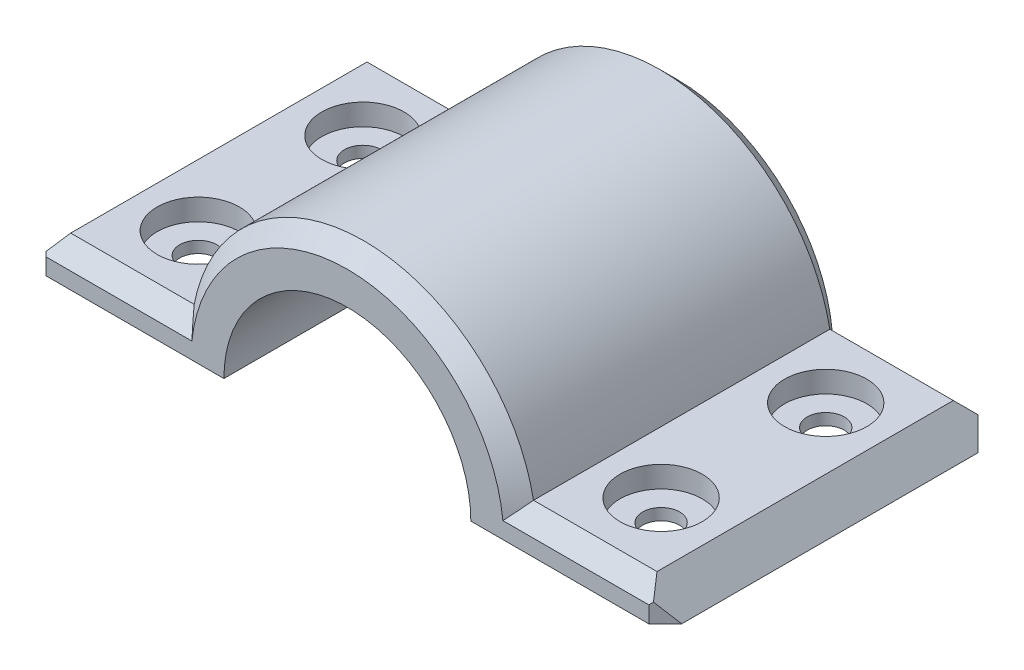
SolidWorks part; units mm, degrees
material "ABS"
ref_plane "Piano frontale" through (0, 0, 0) normal (0, 0, 1) x (1, 0, 0)
ref_plane "Piano superiore" through (0, 0, 0) normal (0, 1, 0) x (1, 0, 0)
ref_plane "Piano destro" through (0, 0, 0) normal (1, 0, 0) x (0, 0, -1)
sketch "Schizzo1" plane through (0, 0, 0) normal (0, 0, 1) x (1, 0, 0)
  line L0 (-14.6572, -3.1885) -> (-11, -20) construction
  line L1 (-11, -20) -> (11, -20) construction
  line L2 (11, -20) -> (14.6572, -3.1885) construction
  line L3 (-14.6572, -3.1885) -> (14.6572, -3.1885) construction
  line L4 (0, -20) -> (0, 0) construction
  line L5 (-15, 0) -> (15, 0) construction
  line L8 (-15, 0) -> (-38.6155, 0)
  line L9 (-38.6155, 0) -> (-35.6155, 4)
  line L10 (-35.6155, 4) -> (-20.6155, 4)
  line L11 (15, 0) -> (38.6155, 0)
  line L12 (38.6155, 0) -> (35.6155, 4)
  line L13 (35.6155, 4) -> (20.6155, 4)
  arc A0 (15, 0) -> (-15, 0) centre (0, 0) ccw construction
  arc A1 (20.6155, 4) -> (-20.6155, 4) centre (0, 0) ccw
  arc A2 (15, 0) -> (-15, 0) centre (0, 0) ccw
  arc A3 (-14.6572, -3.1885) -> (-15, 0) centre (0, 0) cw construction
  arc A4 (14.6572, -3.1885) -> (15, 0) centre (0, 0) ccw construction
  point P8 (0, -3.1885)
  dimension "D2" = 15
  dimension "D4" = 6
  dimension "D1" = 22
  dimension "D3" = 20
  dimension "D5" = 4
  dimension "D6" = 15
  dimension "D7" = 3
extrude "Estrusione-Estrusione1" add sketch "Schizzo1" along normal blind 40
sketch "Schizzo2" plane through (0, 4, 0) normal (0, 1, 0) x (1, 0, 0)
  line L0 (-28.1155, -30) -> (-28.1155, -10) construction
  line L1 (-28.1155, -10) -> (28.1155, -10) construction
  line L2 (28.1155, -10) -> (28.1155, -30) construction
  line L3 (28.1155, -30) -> (-28.1155, -30) construction
  line L5 (-28.1155, -30) -> (-28.1155, -40) construction
  line L6 (-20.6155, -40) -> (-35.6155, -40) construction
  line L8 (-35.6155, -20) -> (-28.1155, -20) construction
  line L9 (-35.6155, -40) -> (-35.6155, 0) construction
  line L11 (28.1155, -10) -> (28.1155, 0) construction
  line L12 (35.6155, 0) -> (20.6155, 0) construction
  line L14 (-20.6155, 0) -> (-35.6155, 0) construction
  point P0 (-28.1155, -10)
  point P2 (-28.1155, -30)
  point P4 (28.1155, -30)
  point P6 (28.1155, -10)
  dimension "D1" = 10
hole_wizard "Foro lamato per Vite M4 a testa cilindrica-1" positions "Schizzo2" profile "Schizzo3" counterbore size "M4" standard "DIN"
sketch "Schizzo3" plane through (-28.1155, 4, 10) normal (1, 0, 0) x (0, 0, 1)
  line L0 (0, 0) -> (0, 81.3519)
  line L1 (0, 81.3519) -> (2.25, 80)
  line L2 (2.25, 80) -> (2.25, 2.6)
  line L3 (2.25, 2.6) -> (5, 2.6)
  line L4 (5, 2.6) -> (5, 0)
  line L5 (5, 0) -> (0, 0)
  line L10 (0, 81.3519) -> (-2.25, 80) construction
  line L11 (0, -6.35) -> (0, 107.95) construction
  dimension "Hole Dia." = 4.5
  dimension "Hole Depth" = 80
  dimension "C'Bore Dia." = 10
  dimension "C'Bore Depth" = 2.6
  dimension "Drill Angle" = 118
chamfer "Smusso1" distance 2 angle 45 6 edges at (28.1155, 4, 0) (0, 21, 0) (-28.1155, 4, 0) (28.1155, 4, 40) (-28.1155, 4, 40) (0, 21, 40)
sketch "Schizzo4" plane through (0, 0, 0) normal (0, -1, 0) x (1, 0, 0)
  line L0 (-38.6155, 38) -> (-36.6155, 40)
  line L1 (-38.6155, 40) -> (-38.6155, 0) construction
  line L2 (-38.6155, 40) -> (-15, 40) construction
  line L3 (-36.6155, 40) -> (-38.6155, 40)
  line L4 (-38.6155, 40) -> (-38.6155, 38)
  line L5 (-38.6155, 2) -> (-36.6155, 0)
  line L6 (-38.6155, 0) -> (-15, 0) construction
  line L7 (-36.6155, 0) -> (-38.6155, 0)
  line L8 (-38.6155, 0) -> (-38.6155, 2)
  line L9 (36.6155, 0) -> (38.6155, 2)
  line L10 (15, 0) -> (38.6155, 0) construction
  line L11 (38.6155, 40) -> (38.6155, 0) construction
  line L12 (38.6155, 2) -> (38.6155, 0)
  line L13 (38.6155, 0) -> (36.6155, 0)
  line L14 (36.6155, 40) -> (38.6155, 40)
  line L15 (15, 40) -> (38.6155, 40) construction
  line L16 (38.6155, 40) -> (38.6155, 38)
  line L17 (38.6155, 38) -> (36.6155, 40)
  dimension "D1" = 2
extrude "Taglio-Estrusione1" cut sketch "Schizzo4" against normal blind 10
